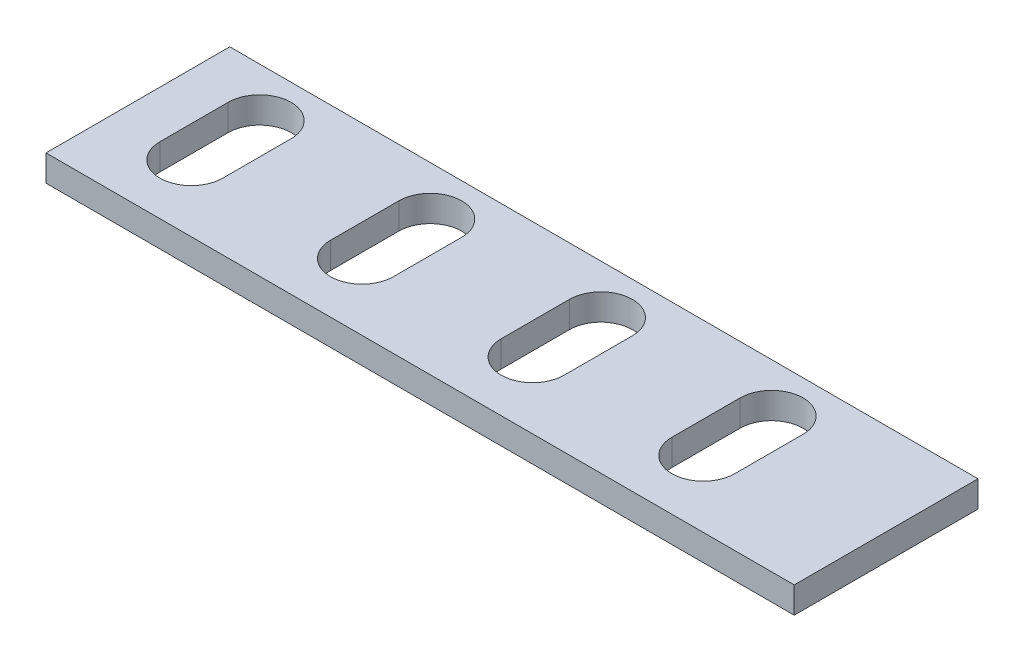
SolidWorks part; units mm, degrees
ref_plane "Front Plane" through (0, 0, 0) normal (0, 0, 1) x (1, 0, 0)
ref_plane "Top Plane" through (0, 0, 0) normal (0, 1, 0) x (1, 0, 0)
ref_plane "Right Plane" through (0, 0, 0) normal (1, 0, 0) x (0, 0, -1)
sketch "Sketch1" plane through (0, 0, 0) normal (0, 1, 0) x (1, 0, 0)
  line L1 (-321.2387, 92.0899) -> (248.7613, 92.0899)
  line L2 (-321.2387, 92.0899) -> (-321.2387, -47.9101)
  line L3 (-321.2387, -47.9101) -> (248.7613, -47.9101)
  line L4 (248.7613, 92.0899) -> (248.7613, -47.9101)
  line L5 (-261.2387, 54.8237) -> (-261.2387, 2.8237) construction
  line L6 (-237.2387, 54.8237) -> (-237.2387, 2.8237)
  line L7 (-285.2387, 54.8237) -> (-285.2387, 2.8237)
  line L8 (-261.2387, 78.8237) -> (-213.6467, 78.8237) construction
  line L9 (-131.2387, 54.8237) -> (-131.2387, 2.8237) construction
  line L10 (-107.2387, 54.8237) -> (-107.2387, 2.8237)
  line L11 (-155.2387, 54.8237) -> (-155.2387, 2.8237)
  line L12 (-1.2387, 54.8237) -> (-1.2387, 2.8237) construction
  line L13 (22.7613, 54.8237) -> (22.7613, 2.8237)
  line L14 (-25.2387, 54.8237) -> (-25.2387, 2.8237)
  line L15 (128.7613, 54.8237) -> (128.7613, 2.8237) construction
  line L16 (152.7613, 54.8237) -> (152.7613, 2.8237)
  line L17 (104.7613, 54.8237) -> (104.7613, 2.8237)
  line L18 (-261.2387, -21.1763) -> (-213.6467, -21.1763) construction
  arc A0 (-237.2387, 54.8237) -> (-285.2387, 54.8237) centre (-261.2387, 54.8237) ccw
  arc A1 (-285.2387, 2.8237) -> (-237.2387, 2.8237) centre (-261.2387, 2.8237) ccw
  arc A2 (-107.2387, 54.8237) -> (-155.2387, 54.8237) centre (-131.2387, 54.8237) ccw
  arc A3 (-155.2387, 2.8237) -> (-107.2387, 2.8237) centre (-131.2387, 2.8237) ccw
  arc A4 (22.7613, 54.8237) -> (-25.2387, 54.8237) centre (-1.2387, 54.8237) ccw
  arc A5 (-25.2387, 2.8237) -> (22.7613, 2.8237) centre (-1.2387, 2.8237) ccw
  arc A6 (152.7613, 54.8237) -> (104.7613, 54.8237) centre (128.7613, 54.8237) ccw
  arc A7 (104.7613, 2.8237) -> (152.7613, 2.8237) centre (128.7613, 2.8237) ccw
  point P9 (-261.2387, 28.8237)
  point P20 (-131.2387, 28.8237)
  point P27 (-1.2387, 28.8237)
  point P34 (128.7613, 28.8237)
  dimension "D5" = 130
  dimension "D1" = 570
  dimension "D2" = 140
  dimension "D3" = 52
  dimension "D4" = 48
  dimension "D6" = 60
  dimension "D8" = 100
  dimension "D7" = 4
extrude "Boss-Extrude1" add sketch "Sketch1" along normal blind 20
